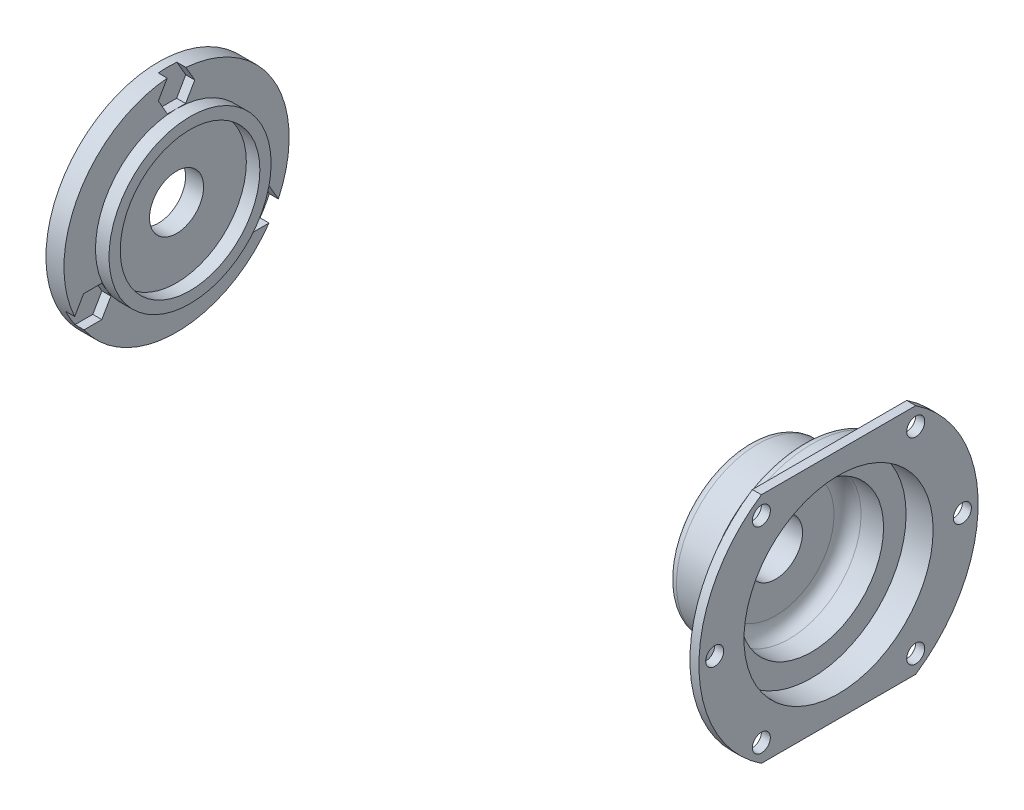
SolidWorks part; units mm, degrees
ref_plane "Front Plane" through (0, 0, 0) normal (0, 0, 1) x (1, 0, 0)
ref_plane "Top Plane" through (0, 0, 0) normal (0, 1, 0) x (1, 0, 0)
ref_plane "Right Plane" through (0, 0, 0) normal (1, 0, 0) x (0, 0, -1)
sketch "Sketch1" plane through (0, 0, 0) normal (1, 0, 0) x (0, 0, -1)
  circle A0 centre (0, 0) radius 25
  dimension "D1" = 50
extrude "Boss-Extrude1" add sketch "Sketch1" along normal blind 4
sketch "Sketch2" plane through (4, 0, 0) normal (1, 0, 0) x (0, 0, -1)
  line L0 (0, 25) -> (0, 18) construction
  line L1 (14.5781, -10.75) -> (16.5988, -14.25)
  line L2 (2.0207, 18) -> (4.0415, 21.5)
  line L3 (4.0415, 21.5) -> (2.0207, 25)
  line L4 (2.0207, 25) -> (-2.0207, 25)
  line L5 (-2.0207, 25) -> (-4.0415, 21.5)
  line L6 (-4.0415, 21.5) -> (-2.0207, 18)
  line L7 (-2.0207, 18) -> (2.0207, 18)
  line L8 (16.5988, -14.25) -> (20.6403, -14.25)
  line L9 (20.6403, -14.25) -> (22.661, -10.75)
  line L10 (22.661, -10.75) -> (20.6403, -7.25)
  line L11 (20.6403, -7.25) -> (16.5988, -7.25)
  line L12 (16.5988, -7.25) -> (14.5781, -10.75)
  line L13 (-16.5988, -7.25) -> (-20.6403, -7.25)
  line L14 (-20.6403, -7.25) -> (-22.661, -10.75)
  line L15 (-22.661, -10.75) -> (-20.6403, -14.25)
  line L16 (-20.6403, -14.25) -> (-16.5988, -14.25)
  line L17 (-16.5988, -14.25) -> (-14.5781, -10.75)
  line L18 (-14.5781, -10.75) -> (-16.5988, -7.25)
  circle A0 centre (0, 0) radius 25 construction
  circle A1 centre (0, 21.5) radius 3.5 construction
  point P28 (0, 0)
  dimension "D1" = 7
  dimension "D2" = 7
  dimension "D3" = 3
extrude "Cut-Extrude2" cut sketch "Sketch2" against normal blind 2
sketch "Sketch3" plane through (4, 0, 0) normal (1, 0, 0) x (0, 0, -1)
  circle A0 centre (0, 0) radius 18
  circle A1 centre (0, 0) radius 15.5
  dimension "D1" = 36
  dimension "D2" = 31
extrude "Boss-Extrude2" add sketch "Sketch3" along normal blind 3 contours A0 | A1
sketch "Sketch4" plane through (4, 0, 0) normal (1, 0, 0) x (0, 0, -1)
  circle A0 centre (0, 0) radius 6
  dimension "D1" = 12
extrude "Boss-Extrude3" add sketch "Sketch4" along normal blind 127
sketch "Sketch5" plane through (131, 0, 0) normal (1, 0, 0) x (0, 0, -1)
  circle A0 centre (0, 0) radius 18
  dimension "D1" = 36
extrude "Boss-Extrude4" add sketch "Sketch5" along normal blind 12
sketch "Sketch6" plane through (143, 0, 0) normal (1, 0, 0) x (0, 0, -1)
  circle A0 centre (0, 0) radius 24
  dimension "D1" = 48
extrude "Boss-Extrude5" add sketch "Sketch6" along normal blind 6
sketch "Sketch7" plane through (149, 0, 0) normal (1, 0, 0) x (0, 0, -1)
  line L0 (0, 25) -> (0, -25) construction
  line L1 (17.1359, 25.8333) -> (-17.1359, 25.8333)
  line L2 (0, 0) -> (-7.1464, 0) construction
  line L3 (17.1359, -25.8333) -> (-17.1359, -25.8333)
  line L4 (25, 0) -> (31, 0) construction
  arc A0 (-17.1359, 25.8333) -> (-17.1359, -25.8333) centre (0, 0) ccw
  arc A1 (17.1359, -25.8333) -> (17.1359, 25.8333) centre (0, 0) ccw
  arc A2 (22.6114, -10.6641) -> (2.0703, 24.9141) centre (0, 0) ccw construction
  point P5 (0, 0)
  point P21 (0, 0)
  dimension "D1" = 62
  dimension "D2" = 50
extrude "Boss-Extrude6" add sketch "Sketch7" along normal blind 2
sketch "Sketch9" plane through (151, 0, 0) normal (1, 0, 0) x (0, 0, -1)
  line L0 (0, 0) -> (0, 5.6047) construction
  line L1 (17.1359, 25.8333) -> (-17.1359, 25.8333) construction
  line L2 (0, 0) -> (-19.0664, 0) construction
  circle A0 centre (0, 0) radius 25 construction
  circle A1 centre (27.5, 0) radius 2
  circle A2 centre (-27.5, 0) radius 2
  circle A3 centre (-17.1359, 21.8333) radius 2
  circle A4 centre (17.1359, 21.8333) radius 2
  circle A5 centre (17.1359, -21.8333) radius 2
  circle A6 centre (-17.1359, -21.8333) radius 2
  dimension "D1" = 50
  dimension "D2" = 4
  dimension "D3" = 27.5
  dimension "D4" = 4
  dimension "D5" = 4
extrude "Cut-Extrude3" cut sketch "Sketch9" against normal blind 2
fillet "Fillet1" radius 2 2 edges at (143, 0, -24) (131, 0, -18)
fillet "Fillet2" radius 1 1 edges at (143, 0, -18)
ref_plane "Plane1" through (75.5, 0, 0) normal (1, 0, 0) x (0, 0, -1)
sketch "Sketch10" plane through (75.5, 0, 0) normal (1, 0, 0) x (0, 0, -1)
  circle A0 centre (0, 0) radius 20
  dimension "D1" = 40
extrude "Boss-Extrude7" add sketch "Sketch10" along normal blind 5 from offset 5
sketch "Sketch11" plane through (75.5, 0, 0) normal (1, 0, 0) x (0, 0, -1)
  circle A2 centre (0, 0) radius 20
  circle A3 centre (0, 0) radius 20
  dimension "D1" = 0
extrude "Boss-Extrude8" add sketch "Sketch11" against normal blind 5 from offset 5 offset against normal yes
sketch "Sketch12" plane through (75.5, 0, 0) normal (1, 0, 0) x (0, 0, -1)
  circle A0 centre (0, 0) radius 17.5
  dimension "D1" = 35
extrude "Boss-Extrude9" add sketch "Sketch12" along normal mid plane 10
sketch "Sketch13" plane through (151, 0, 0) normal (1, 0, 0) x (0, 0, -1)
  circle A0 centre (0, 0) radius 6
  dimension "D1" = 12
sketch "Sketch14" plane through (0, 0, 0) normal (0, 0, 1) x (1, 0, 0)
  line L0 (7, 0) -> (7, 6)
  line L1 (7, -18) -> (7, 18) construction
  line L2 (65.5, 6) -> (4, 6) construction
  line L3 (7, 6) -> (65.5, 6)
  line L4 (65.5, 20) -> (65.5, -20) construction
  line L5 (65.5, 6) -> (65.5, -6)
  line L6 (65.5, -6) -> (7, -6)
  line L7 (4, -6) -> (65.5, -6) construction
  line L8 (7, -6) -> (7, 0)
extrude "Cut-Extrude4" cut sketch "Sketch14" against normal mid plane 15 contours L8 L0 L3 L5 L6
sketch "Sketch15" plane through (0, 0, 0) normal (0, 0, 1) x (1, 0, 0)
  line L1 (65.4776, 20.4609) -> (131, 20.4609)
  line L2 (65.4776, 20.4609) -> (65.4776, -22.8345)
  line L3 (65.4776, -22.8345) -> (131, -22.8345)
  line L4 (131, 20.4609) -> (131, -22.8345)
extrude "Cut-Extrude5" cut sketch "Sketch15" against normal mid plane 65
extrude "Cut-Extrude6" cut sketch "Sketch13" against normal blind 35
sketch "Sketch17" plane through (7, 0, 0) normal (1, 0, 0) x (0, 0, -1)
  circle A0 centre (0, 0) radius 6
extrude "Cut-Extrude8" cut sketch "Sketch17" against normal up to surface (3 mm away) up to face at (4, 0, -6)
sketch "Sketch18" plane through (4, 0, 0) normal (1, 0, 0) x (0, 0, -1)
  circle A0 centre (0, 0) radius 6
extrude "Cut-Extrude9" cut sketch "Sketch18" against normal blind 13 contours A0
sketch "Sketch19" plane through (151, 0, 0) normal (1, 0, 0) x (0, 0, -1)
  circle A0 centre (0, 0) radius 24
  dimension "D1" = 48
extrude "Cut-Extrude10" cut sketch "Sketch19" against normal blind 6
sketch "Sketch20" plane through (145, 0, 0) normal (1, 0, 0) x (0, 0, -1)
  circle A0 centre (0, 0) radius 16
  dimension "D1" = 32
extrude "Cut-Extrude11" cut sketch "Sketch20" against normal blind 8
fillet "Fillet3" radius 3 1 edges at (137, 0, -16)
sketch "Sketch21" plane through (145, 0, 0) normal (1, 0, 0) x (0, 0, -1)
  circle A0 centre (0, 0) radius 24
  circle A1 centre (0, 0) radius 21
  dimension "D1" = 42
extrude "Boss-Extrude10" add sketch "Sketch21" along normal up to surface (6 mm away) up to face at (151, 0, -24)
